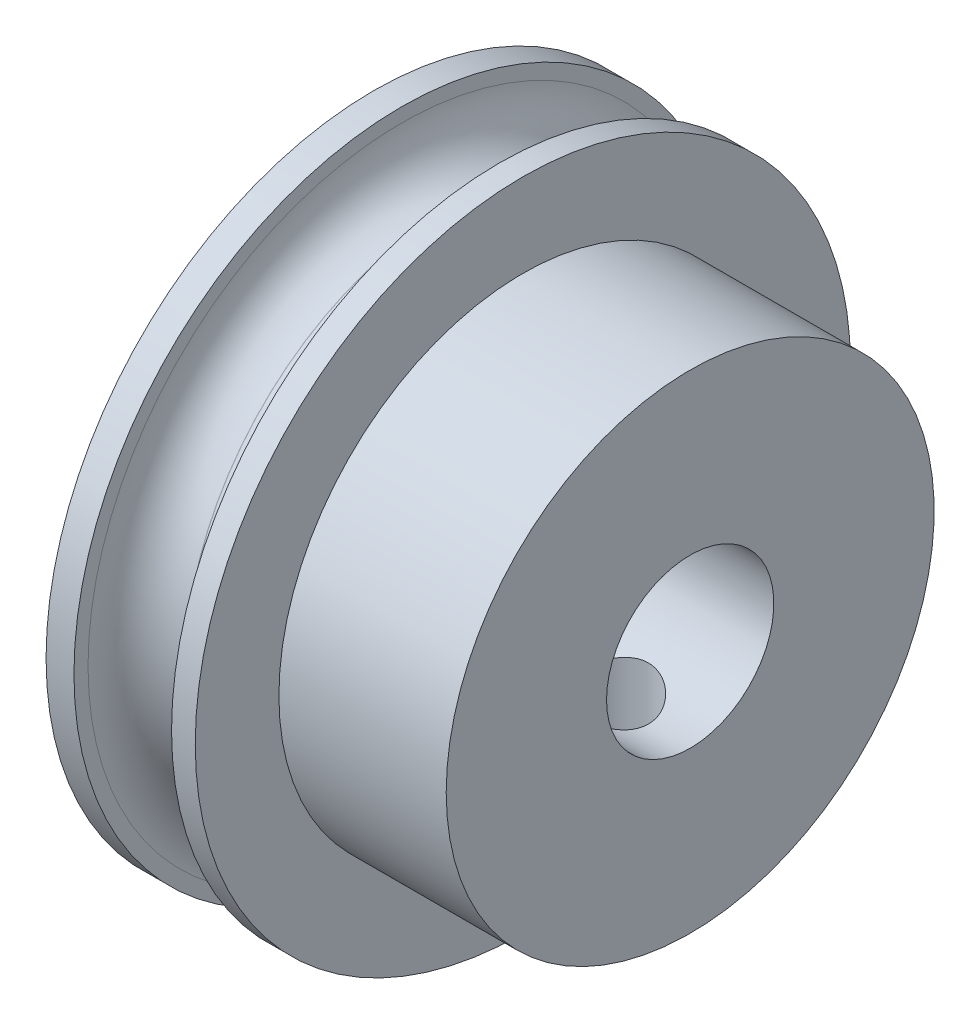
SolidWorks part; units mm, degrees
ref_plane "Спереди" through (0, 0, 0) normal (0, 0, 1) x (1, 0, 0)
ref_plane "Сверху" through (0, 0, 0) normal (0, 1, 0) x (1, 0, 0)
ref_plane "Справа" through (0, 0, 0) normal (1, 0, 0) x (0, 0, -1)
sketch "ы" plane through (0, 0, 0) normal (0, 0, 1) x (1, 0, 0)
  line L0 (0, 6) -> (22.7, 6)
  line L1 (22.7, 6) -> (22.7, 17.5)
  line L2 (22.7, 17.5) -> (10.7, 17.5)
  line L3 (10.7, 17.5) -> (10.7, 23.5)
  line L4 (10.7, 23.5) -> (9, 23.5)
  line L5 (9, 23.5) -> (9, 22.49)
  line L6 (5.51, 19) -> (5.49, 19)
  line L7 (2, 22.49) -> (2, 23.5)
  line L8 (2, 23.5) -> (0, 23.5)
  line L9 (0, 23.5) -> (0, 6)
  line L10 (0, 0) -> (31.5833, 0) construction
  arc A0 (5.49, 19) -> (2, 22.49) centre (5.49, 22.49) cw
  arc A1 (9, 22.49) -> (5.51, 19) centre (5.51, 22.49) cw
  point P13 (15.7917, 0)
  point P18 (2, 19)
  point P21 (9, 19)
  dimension "D5" = 3.49
  dimension "D1" = 6
  dimension "D2" = 17.5
  dimension "D3" = 23.5
  dimension "D4" = 12
  dimension "D6" = 1.7
  dimension "D7" = 2
  dimension "D8" = 7
  dimension "D9" = 4.5
revolve "Повернуть1" add sketch "ы" angle 360 about L10
sketch "Эскиз2" plane through (0, 0, 0) normal (0, 1, 0) x (1, 0, 0)
  line L0 (16.7, 17.5) -> (16.7, -22.5974) construction
  line L1 (22.7, 17.5) -> (10.7, 17.5) construction
  circle A0 centre (16.7, 0) radius 3
  dimension "D1" = 6
extrude "Вырез-Вытянуть1" cut sketch "Эскиз2" against normal up to next
